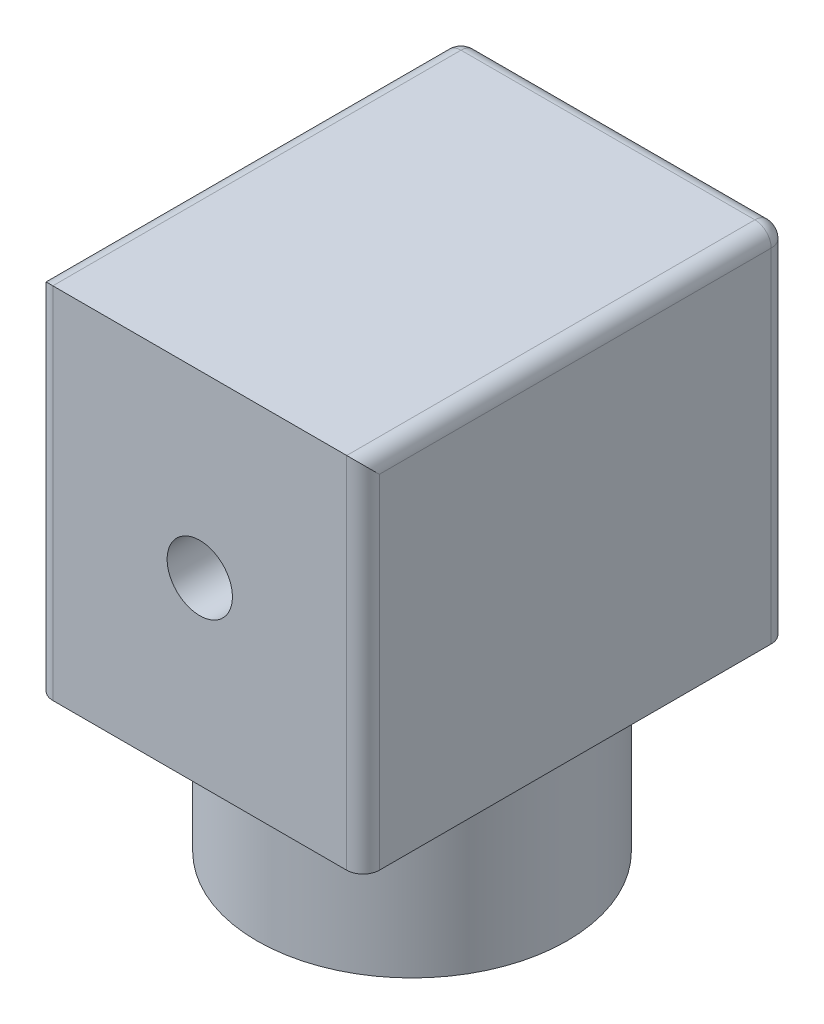
SolidWorks part; units mm, degrees
ref_plane "Front Plane" through (0, 0, 0) normal (0, 0, 1) x (1, 0, 0)
ref_plane "Top Plane" through (0, 0, 0) normal (0, 1, 0) x (1, 0, 0)
ref_plane "Right Plane" through (0, 0, 0) normal (1, 0, 0) x (0, 0, -1)
sketch "Sketch1" plane through (0, 0, 0) normal (0, 0, 1) x (1, 0, 0)
  line L1 (50, 55) -> (-50, 55)
  line L2 (50, 55) -> (50, -55)
  line L3 (50, -55) -> (-50, -55)
  line L4 (-50, 55) -> (-50, -55)
  line L5 (50, 55) -> (-50, -55) construction
  line L6 (50, -55) -> (-50, 55) construction
  point P0 (0, 0)
  dimension "D1" = 110
  dimension "D2" = 100
extrude "Boss-Extrude1" add sketch "Sketch1" along normal blind 130
sketch "Sketch2" plane through (0, -55, 0) normal (0, 1, 0) x (1, 0, 0)
  line L0 (-50, -130) -> (-50, 0) construction
  circle A0 centre (0, -65) radius 47.5
  point P7 (-50, -65)
  dimension "D2" = 95
extrude "Boss-Extrude2" add sketch "Sketch2" against normal blind 50
sketch "Sketch4" plane through (0, -105, 0) normal (0, -1, 0) x (1, 0, 0)
  circle A0 centre (0, 65) radius 10
  dimension "D1" = 20
extrude "Cut-Extrude3" cut sketch "Sketch4" against normal blind 20
sketch "Sketch5" plane through (0, 0, 130) normal (0, 0, 1) x (1, 0, 0)
  circle A0 centre (0, 0) radius 10
  dimension "D1" = 20
extrude "Cut-Extrude4" cut sketch "Sketch5" against normal blind 20
ref_plane "Plane1" through (0, -345, 0) normal (0, 1, 0) x (1, 0, 0)
fillet "Fillet1" radius 5 7 edges at (50, 0, 130) (-50, 0, 130) (50, 0, 0) (-50, 0, 0) (50, 55, 65) (0, 55, 0) (-50, 55, 65)
sketch "Sketch6" plane through (0, 0, 0) normal (0, 1, 0) x (1, 0, 0)
  line L0 (0, -67.5) -> (-89.4597, -67.5) construction
  line L1 (0, -67.5) -> (0, 21.9597) construction
  line L2 (-45, -5) -> (-45, -130) construction
  text T0 "X1" font "Century Gothic" height 10
  text T1 "Z1" font "Century Gothic" height 10
  point P6 (-84.8047, -67.5)
  point P7 (-45, -67.5)
  point P8 (0, -14.6562)
  point P10 (0, 21.9597)
sketch "Sketch7" plane through (0, 0, 0) normal (1, 0, 0) x (0, 0, -1)
  line L0 (-67.5, 0) -> (-67.5, 89.4597) construction
  line L2 (-67.5, 0) -> (21.9597, 0) construction
  text T0 "Y1" font "Century Gothic" height 10
